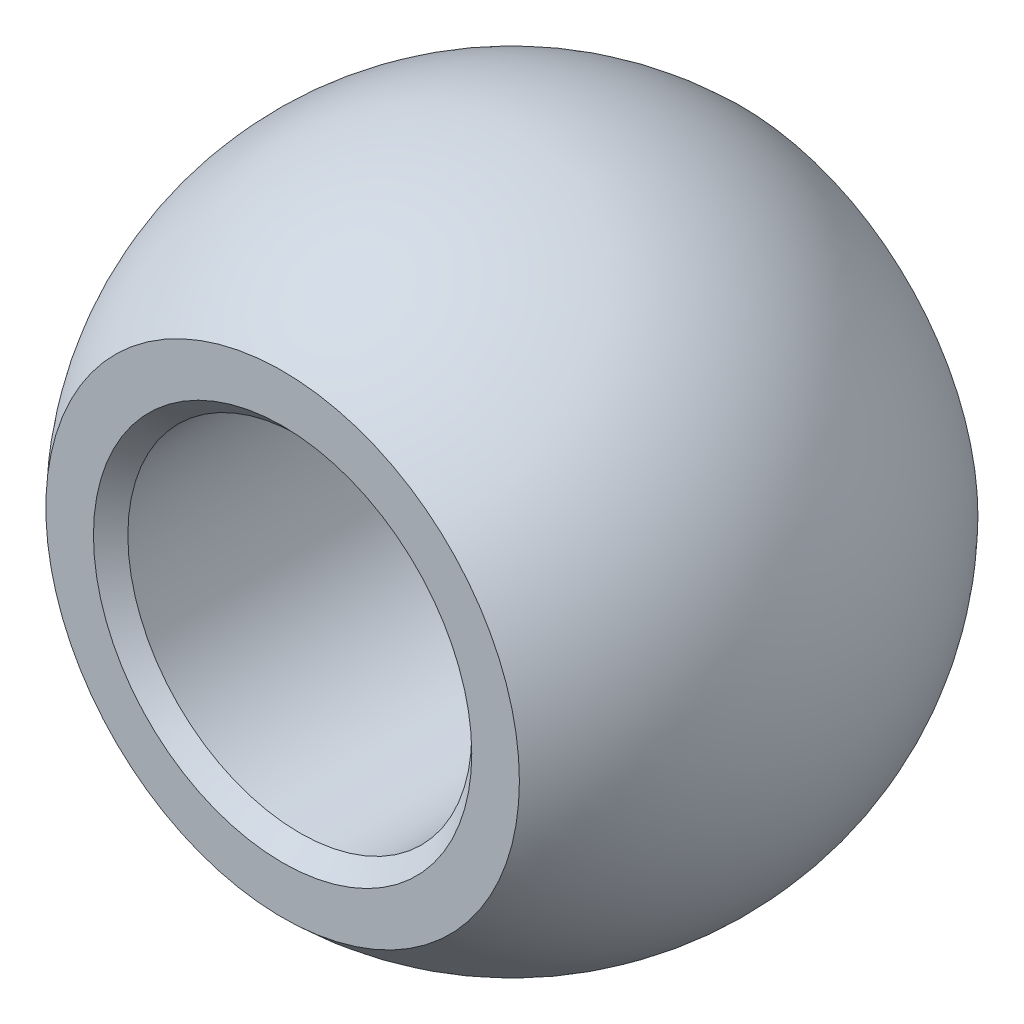
SolidWorks part; units mm, degrees
ref_plane "Front" through (0, 0, 0) normal (0, 0, 1) x (1, 0, 0)
ref_plane "Top" through (0, 0, 0) normal (0, 1, 0) x (1, 0, 0)
ref_plane "Right" through (0, 0, 0) normal (1, 0, 0) x (0, 0, -1)
sketch "Sketch1" plane through (0, 0, 0) normal (0, 0, 1) x (1, 0, 0)
  line L0 (0, 0) -> (0, -31.75)
  line L1 (0, -31.75) -> (4.7625, -31.75)
  line L2 (4.7625, -31.75) -> (4.7625, 0)
  line L3 (4.7625, 0) -> (0, 0)
  line L5 (0, 30.1625) -> (0, 0) construction
  line L6 (0, 30.1625) -> (12.7, 30.1625) construction
  line L7 (12.7, 30.1625) -> (12.7, 17.4625) construction
  line L8 (-4.7625, -31.75) -> (-4.7625, 0) construction
  line L9 (4.8772, -31.6838) -> (4.8772, -32.743)
  line L10 (4.8772, -32.743) -> (3.9599, -32.2134)
  line L11 (4.0745, -32.2796) -> (4.0745, -32.1472)
  line L12 (3.9599, -32.2134) -> (4.8772, -31.6838)
  line L13 (4.8198, -31.7169) -> (4.8198, -32.7099)
  line L14 (4.8772, -32.2134) -> (4.7625, -32.2134)
  line L15 (4.7625, -31.75) -> (4.7625, -32.6768)
  line L16 (3.9599, -32.2134) -> (4.0745, -32.2134)
  arc A0 (8.3507, 7.894) -> (0, 30.1625) centre (0, 17.4625) ccw construction
  circle A1 centre (0, 17.4625) radius 4.7625 construction
  circle A2 centre (0, 17.4625) radius 9.1281 construction
  circle A3 centre (0, 17.4625) radius 9.2194 construction
  arc A4 (4.7625, 0) -> (8.3507, 7.894) centre (15.24, 0) cw construction
  point P24 (0, 26.5906)
  point P26 (4.7625, -32.2134)
  point P28 (4.8198, -32.2134)
  dimension "A" = 9.525
  dimension "Ball Dia" = 18.2562
  dimension "B" = 25.4
  dimension "D1" = 18.4388
  dimension "D" = 49.2125
  dimension "E" = 31.75
  dimension "Thread Dia" = 9.525
  dimension "D2" = 60
  dimension "Pitch" = 1.0592
  dimension "D4" = 0.1324
sketch "Sketch2" plane through (0, 0, 0) normal (1, 0, 0) x (0, 0, -1)
  line L0 (4.5641, 17.4625) -> (-4.5641, 17.4625)
  line L1 (4.5641, 18.3497) -> (0, 17.4625) construction
  line L2 (4.5641, 16.5753) -> (0, 17.4625) construction
  line L6 (6.35, 17.4625) -> (-6.35, 17.4625)
  line L7 (0, 12.7) -> (0, 22.225)
  line L8 (0, 30.1625) -> (0, 0) construction
  line L9 (0, 22.225) -> (0, 12.7) construction
  circle A0 centre (0, 17.4625) radius 9.1281
  circle A1 centre (0, 17.4625) radius 12.7
  point P4 (0, 17.4625)
  point P7 (0, 26.5906)
  point P9 (0, 8.3344)
  point P14 (0, 17.4625)
  point P18 (0, 17.4625)
  point P23 (12.7, 17.4625)
  point P25 (-12.7, 17.4625)
  dimension "OAWidth" = 9.1281
  dimension "Swivel" = 22
  dimension "BallWidth" = 12.7
sketch "Sketch15" plane through (0, 0, 0) normal (0, 0, 1) x (1, 0, 0)
  line L0 (0, 30.1625) -> (0, 0) construction
  line L1 (12.7, 30.1625) -> (-12.7, 30.1625)
  line L2 (12.7, 30.1625) -> (12.7, 0)
  line L3 (12.7, 0) -> (-12.7, 0)
  line L4 (-12.7, 30.1625) -> (-12.7, 0)
  line L5 (4.7625, 0) -> (0, 0) construction
  point P5 (0, 30.1625)
sketch "Sketch7" plane through (0, 0, 0) normal (0, 0, 1) x (1, 0, 0)
  line L0 (0, 26.5906) -> (0, 8.3344)
  line L1 (0, 30.1625) -> (0, 0) construction
  line L2 (0, 0) -> (0, 8.3344) construction
  arc A0 (0, 8.3344) -> (0, 26.5906) centre (0, 17.4625) ccw
  circle A1 centre (0, 17.4625) radius 9.1281 construction
revolve "Revolve3" add sketch "Sketch7" angle 360 about L2
sketch "Sketch10" plane through (0, 0, 0) normal (0, 0, 1) x (1, 0, 0)
  circle A0 centre (0, 17.4625) radius 4.7625 construction
  circle A1 centre (0, 17.4625) radius 4.7625
extrude "Cut-Extrude4" cut sketch "Sketch10" against normal through all and the other way through all
sketch "Sketch22" plane through (0, 0, 0) normal (0, 0, 1) x (1, 0, 0)
  line L0 (-12.7, 30.1625) -> (-12.7, 0) construction
  line L1 (12.7, 0) -> (-12.7, 0) construction
  line L2 (12.7, 30.1625) -> (12.7, 0) construction
  line L3 (12.7, 30.1625) -> (-12.7, 30.1625) construction
  line L4 (-12.7, 30.1625) -> (-12.7, 0)
  line L5 (12.7, 0) -> (-12.7, 0)
  line L6 (12.7, 30.1625) -> (12.7, 0)
  line L7 (12.7, 30.1625) -> (-12.7, 30.1625)
extrude "Cut-Extrude7" cut sketch "Sketch22" against normal through all from vertex at -6.35 starting at point (0, 17.4625, -6.35)
sketch "Sketch23" plane through (0, 0, 0) normal (0, 0, 1) x (1, 0, 0)
  line L0 (-12.7, 30.1625) -> (-12.7, 0) construction
  line L1 (12.7, 0) -> (-12.7, 0) construction
  line L2 (12.7, 30.1625) -> (12.7, 0) construction
  line L3 (12.7, 30.1625) -> (-12.7, 30.1625) construction
  line L4 (-12.7, 30.1625) -> (-12.7, 0)
  line L5 (12.7, 0) -> (-12.7, 0)
  line L6 (12.7, 30.1625) -> (12.7, 0)
  line L7 (12.7, 30.1625) -> (-12.7, 30.1625)
extrude "Cut-Extrude8" cut sketch "Sketch23" along normal through all from vertex at 6.35 starting at point (0, 17.4625, 6.35)
chamfer "Chamfer2" distance 0.4762 angle 45 2 edges at (4.7625, 17.4625, 6.35) (4.7625, 17.4625, -6.35)
ref_plane "Plane1" through (0, 0, 0) normal (0, 1, 0) x (1, 0, 0)
sketch "Sketch24" plane through (0, 0, 0) normal (0, 0, 1) x (1, 0, 0)
  point P0 (0, 17.4625)
equation "\"D1@Sketch1\"=\"Ball Dia@Sketch1\"*1.01"
equation "\"D1\"= \"A@Sketch1\" / 20"
equation "\"D3\"= \"E@Sketch1\" + .2"
equation "\"D4@Sketch1\"=\"Pitch@Sketch1\"/8"
equation "\"D1@Chamfer2\"=\"A@Sketch1\"/20"
